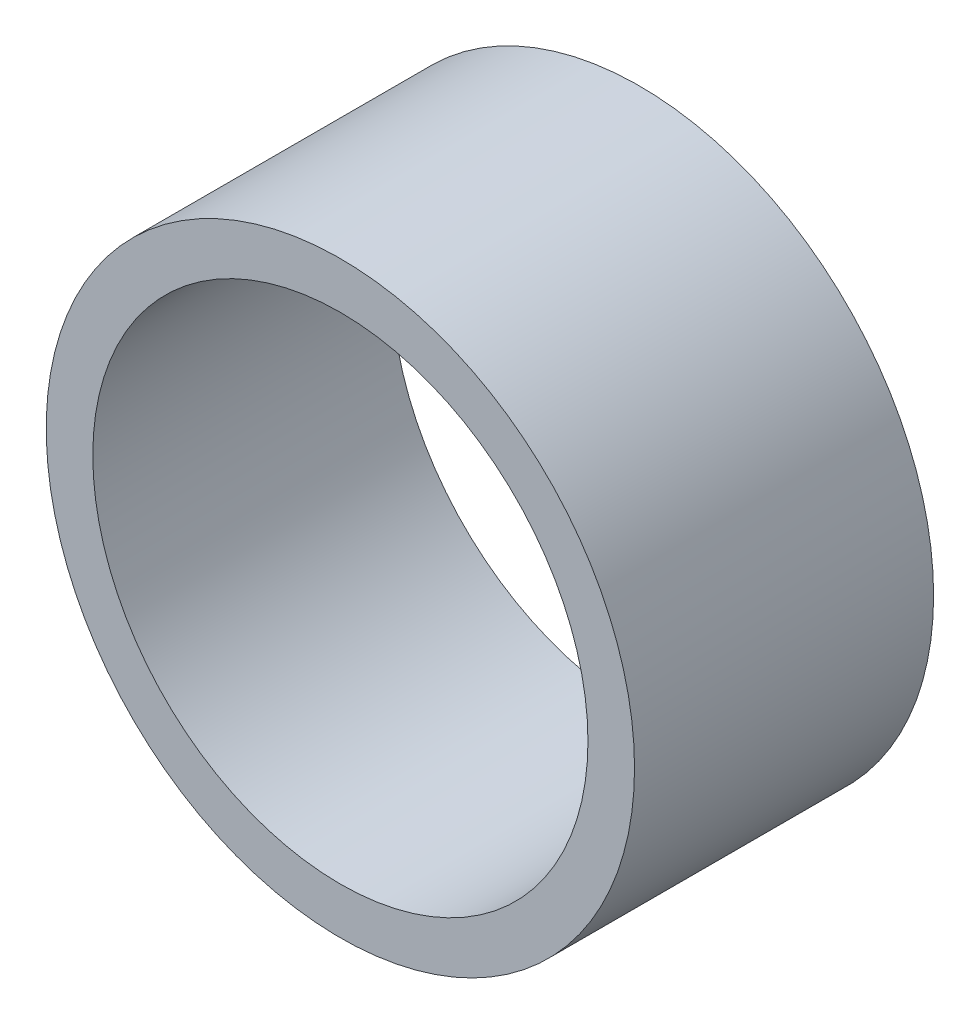
SolidWorks part; units mm, degrees
ref_plane "Front Plane" through (0, 0, 0) normal (0, 0, 1) x (1, 0, 0)
ref_plane "Top Plane" through (0, 0, 0) normal (0, 1, 0) x (1, 0, 0)
ref_plane "Right Plane" through (0, 0, 0) normal (1, 0, 0) x (0, 0, -1)
sketch "Sketch1" plane through (0, 0, 0) normal (0, 0, 1) x (1, 0, 0)
  circle A0 centre (0, 0) radius 15.15
  circle A1 centre (0, 0) radius 18
  dimension "D1" = 30.3
  dimension "D2" = 36
extrude "Boss-Extrude1" add sketch "Sketch1" along normal mid plane 18.3 contours A0 | A1
